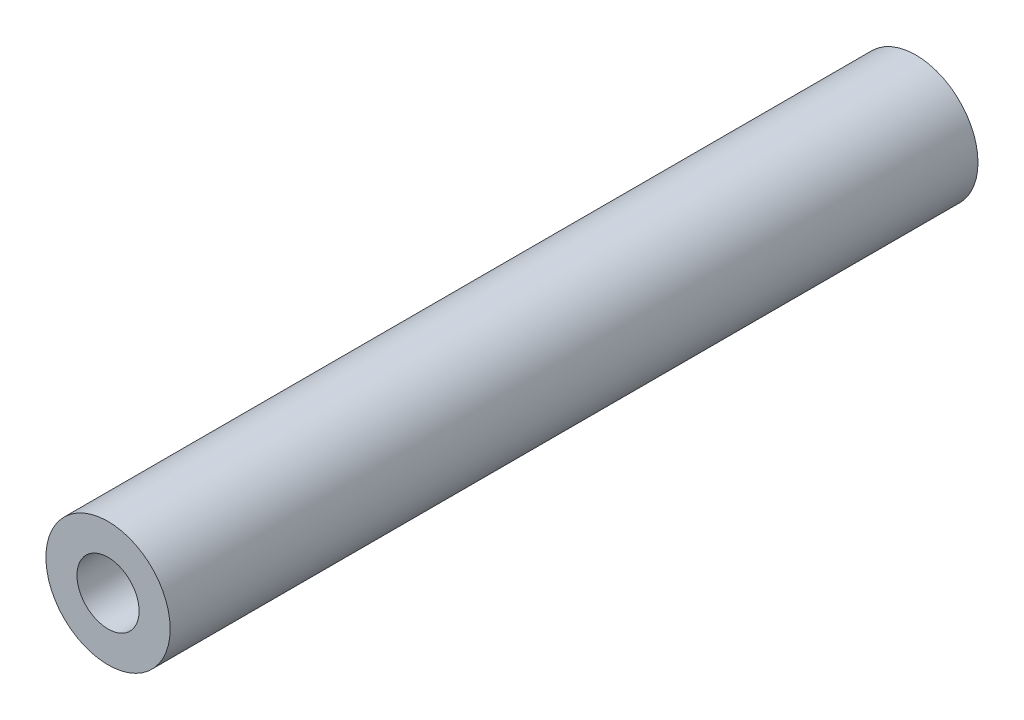
SolidWorks part; units mm, degrees
ref_plane "Front Plane" through (0, 0, 0) normal (0, 0, 1) x (1, 0, 0)
ref_plane "Top Plane" through (0, 0, 0) normal (0, 1, 0) x (1, 0, 0)
ref_plane "Right Plane" through (0, 0, 0) normal (1, 0, 0) x (0, 0, -1)
sketch "Sketch1" plane through (0, 0, 0) normal (0, 0, 1) x (1, 0, 0)
  circle A0 centre (0, 0) radius 5
  circle A1 centre (0, 0) radius 2.5
  dimension "D1" = 5
  dimension "D2" = 10
extrude "Boss-Extrude1" add sketch "Sketch1" along normal blind 65
